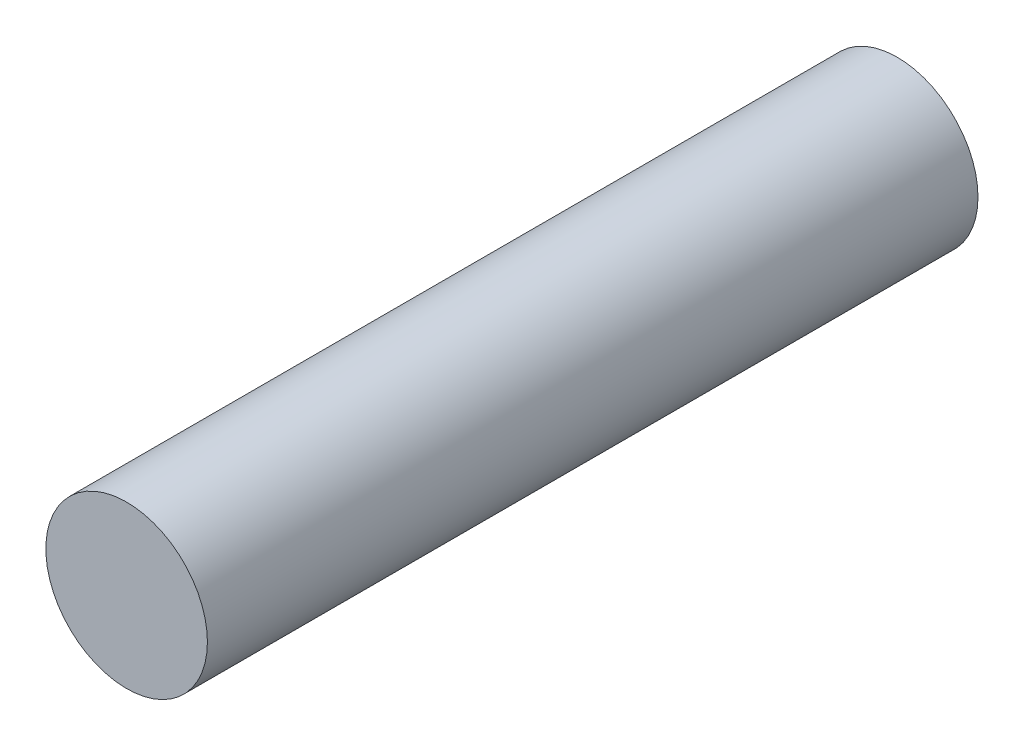
SolidWorks part; units mm, degrees
material "Хромированная нержавеющая сталь"
ref_plane "Спереди" through (0, 0, 0) normal (0, 0, 1) x (1, 0, 0)
ref_plane "Сверху" through (0, 0, 0) normal (0, 1, 0) x (1, 0, 0)
ref_plane "Справа" through (0, 0, 0) normal (1, 0, 0) x (0, 0, -1)
sketch "Эскиз1" plane through (0, 0, 0) normal (0, 0, 1) x (1, 0, 0)
  circle A0 centre (0, 0) radius 3.25
  dimension "D1" = 6.5
extrude "Бобышка-Вытянуть1" add sketch "Эскиз1" along normal blind 31
